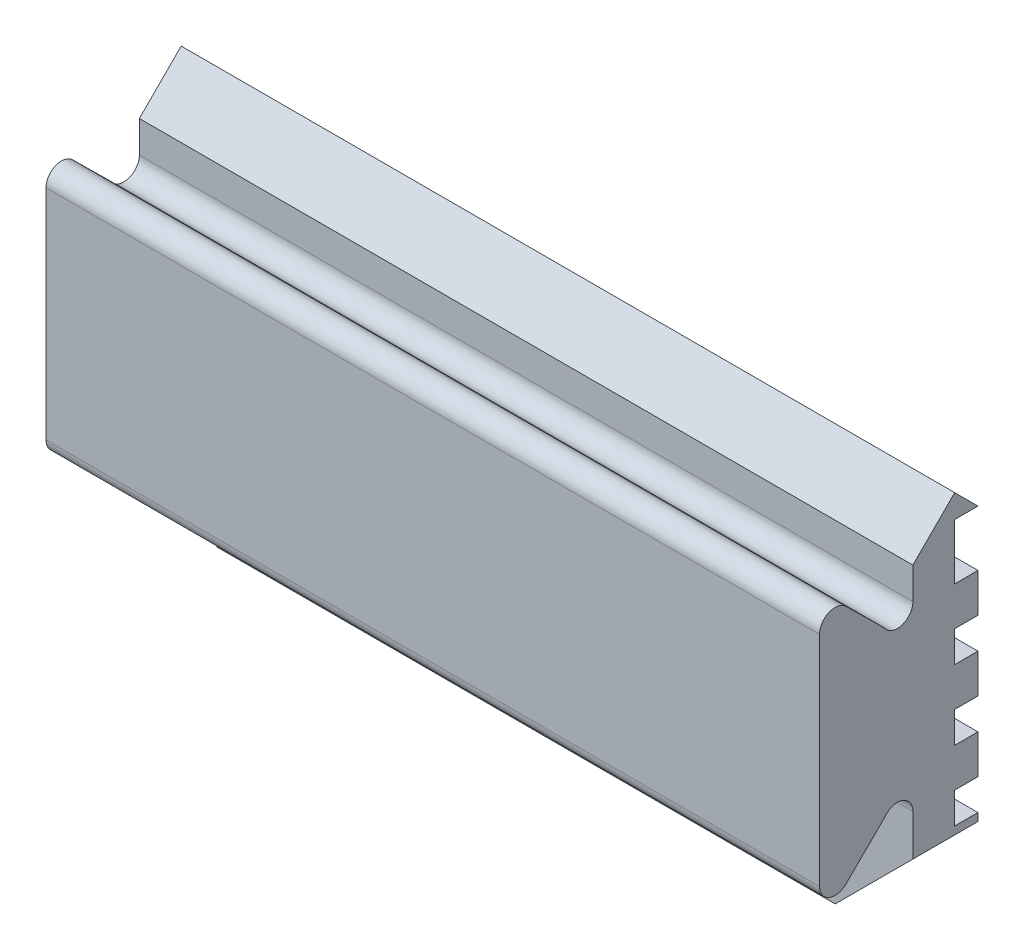
SolidWorks part; units mm, degrees
ref_plane "前视基准面" through (0, 0, 0) normal (0, 0, 1) x (1, 0, 0)
ref_plane "上视基准面" through (0, 0, 0) normal (0, 1, 0) x (1, 0, 0)
ref_plane "右视基准面" through (0, 0, 0) normal (1, 0, 0) x (0, 0, -1)
other "Configuration Table"
sketch "草图1" plane through (0, 0, 0) normal (1, 0, 0) x (0, 0, -1)
  line L0 (-9.8418, 9.874) -> (-12.6045, 12.6044)
  line L1 (-14.3116, 11.8973) -> (-14.3116, -2.1592)
  line L2 (-8.3012, 10.7153) -> (-8.3012, 12.754)
  line L3 (-8.3012, 12.754) -> (-5.6082, 15.447)
  line L4 (-14.3116, 4.8691) -> (-3.3012, 4.8691) construction
  line L5 (-8.3012, -0.9771) -> (-8.3012, -3.0159)
  line L6 (-9.8418, -0.1359) -> (-12.6045, -2.8663)
  line L7 (-8.3012, -3.0159) -> (-8.3012, -8.6409)
  line L8 (-8.3012, -8.6409) -> (-3.3012, -8.6409)
  line L9 (-3.3012, -8.6409) -> (-3.3012, 13.1399)
  line L10 (-3.3012, 13.1399) -> (-5.6082, 15.447)
  arc A0 (-12.6045, 12.6044) -> (-14.3116, 11.8973) centre (-13.3116, 11.8973) ccw
  arc A1 (-10.136, 10.1647) -> (-8.3012, 10.7153) centre (-9.3012, 10.7153) ccw
  arc A2 (-10.136, -0.4266) -> (-8.3012, -0.9771) centre (-9.3012, -0.9771) cw
  arc A3 (-12.6045, -2.8663) -> (-14.3116, -2.1592) centre (-13.3116, -2.1592) cw
extrude "凸台-拉伸1" add sketch "草图1" along normal blind 49.8 contours L4 L1 A3 L6 A2 L5 L7 L8 L9 | L1 L4 L9 L10 L3 L2 A1 L0 A0
chamfer "倒角1" distance 5 angle 45 2 edges at (0, -8.6409, 5.8012) (49.8, -8.6409, 5.8012)
sketch "草图3" plane through (49.8, 0, 0) normal (1, 0, 0) x (0, 0, -1)
  line L0 (-3.3012, 13.1399) -> (-5.6082, 15.447) construction
  line L1 (-4.1082, 13.947) -> (-3.3012, 13.947)
  line L2 (-4.1082, 13.947) -> (-4.1082, -8.6409)
  line L3 (-4.1082, -8.6409) -> (-3.3012, -8.6409)
  line L4 (-3.3012, 13.947) -> (-3.3012, -8.6409)
  dimension "D1" = 1.5
extrude "切除-拉伸1" cut sketch "草图3" against normal blind 49.8
sketch "草图4" plane through (0, 0, 4.1082) normal (0, 0, -1) x (-1, 0, 0)
  line L0 (-49.8, 13.947) -> (-49.8, -3.6409) construction
  line L1 (-49.8, -5.6409) -> (0, -5.6409)
  line L2 (-49.8, -5.6409) -> (-49.8, -7.6409)
  line L3 (-49.8, -7.6409) -> (0, -7.6409)
  line L4 (0, -5.6409) -> (0, -7.6409)
  line L5 (0, 13.947) -> (0, -3.6409) construction
  line L6 (-49.8, -1.1409) -> (0, -1.1409)
  line L7 (-5, -8.6409) -> (-44.8, -8.6409) construction
  line L8 (-49.8, -1.1409) -> (-49.8, -3.1409)
  line L9 (-49.8, -3.1409) -> (0, -3.1409)
  line L10 (0, -1.1409) -> (0, -3.1409)
  line L11 (-49.8, 3.3591) -> (0, 3.3591)
  line L12 (-49.8, 3.3591) -> (-49.8, 1.3591)
  line L13 (-49.8, 1.3591) -> (0, 1.3591)
  line L14 (0, 3.3591) -> (0, 1.3591)
  line L15 (-49.8, 7.8591) -> (0, 7.8591)
  line L16 (-49.8, 7.8591) -> (-49.8, 5.8591)
  line L17 (-49.8, 5.8591) -> (0, 5.8591)
  line L18 (0, 7.8591) -> (0, 5.8591)
  line L19 (-49.8, 12.3591) -> (0, 12.3591)
  line L20 (-49.8, 12.3591) -> (-49.8, 10.3591)
  line L21 (-49.8, 10.3591) -> (0, 10.3591)
  line L22 (0, 12.3591) -> (0, 10.3591)
  dimension "D1" = 2
  dimension "D2" = 1
  dimension "D3" = 5
extrude "切除-拉伸2" cut sketch "草图4" against normal blind 1.5
sketch "草图5" plane through (0, 0, 5.6082) normal (0, 0, -1) x (-1, 0, 0)
  line L0 (0, 13.947) -> (-46.3101, -7.1308)
  line L1 (-45.8, -7.6409) -> (-47.8, -5.6409) construction
  line L2 (-46.3101, -7.1308) -> (-44.8, -8.6409)
  line L3 (-44.8, -8.6409) -> (0, 11.7495)
  line L4 (0, 10.3591) -> (0, 12.3591) construction
  line L5 (0, 11.7495) -> (0, 13.947)
  line L6 (-24.9, 13.947) -> (-24.9, -8.6409) construction
  line L7 (0, 13.947) -> (-49.8, 13.947) construction
  line L8 (-5, -8.6409) -> (-44.8, -8.6409) construction
  line L9 (-49.8, 11.7495) -> (-49.8, 13.947)
  line L10 (-5, -8.6409) -> (-49.8, 11.7495)
  line L11 (-3.4899, -7.1308) -> (-5, -8.6409)
  line L12 (-49.8, 13.947) -> (-3.4899, -7.1308)
  dimension "D1" = 2
extrude "切除-拉伸5" cut sketch "草图5" along normal blind 1.5 contours L10 L9 L12 L11 | L0 L2 L3 L5
sketch "草图6" plane through (0, 0, 4.1082) normal (0, 0, -1) x (-1, 0, 0)
  line L3 (-28.3217, -1.1409) -> (-21.4783, -1.1409)
  line L4 (-21.4783, -1.1409) -> (-24.9, 0.4165)
  line L5 (-24.9, 0.4165) -> (-28.3217, -1.1409)
  line L6 (-28.3217, -1.1409) -> (-21.4783, -1.1409)
  line L7 (-21.4783, -1.1409) -> (-24.9, 0.4165)
  line L8 (-24.9, 0.4165) -> (-28.3217, -1.1409)
  line L10 (-17.7699, 5.8591) -> (-32.0301, 5.8591)
  line L11 (-32.0301, 5.8591) -> (-26.5373, 3.3591)
  line L12 (-26.5373, 3.3591) -> (-23.2627, 3.3591)
  line L13 (-23.2627, 3.3591) -> (-17.7699, 5.8591)
  line L14 (-17.7699, 5.8591) -> (-32.0301, 5.8591)
  line L15 (-32.0301, 5.8591) -> (-26.5373, 3.3591)
  line L16 (-26.5373, 3.3591) -> (-23.2627, 3.3591)
  line L17 (-23.2627, 3.3591) -> (-17.7699, 5.8591)
  dimension "D1" = 0
  dimension "D2" = 0
extrude "切除-拉伸6" cut sketch "草图6" against normal blind 1.5
fillet "圆角1" radius 0.3 12 edges at (38.2087, -5.6409, 4.8582) (11.5913, -5.6409, 4.8582) (8.5478, 7.8591, 4.8582) (41.9171, 10.3591, 4.8582) (7.8829, 10.3591, 4.8582) (41.2522, 7.8591, 4.8582) (31.3653, 3.3591, 4.8582) (12.2561, -3.1409, 4.8582) (18.4347, 3.3591, 4.8582) (22.1431, 1.3591, 4.8582) (37.5439, -3.1409, 4.8582) (27.6569, 1.3591, 4.8582)
